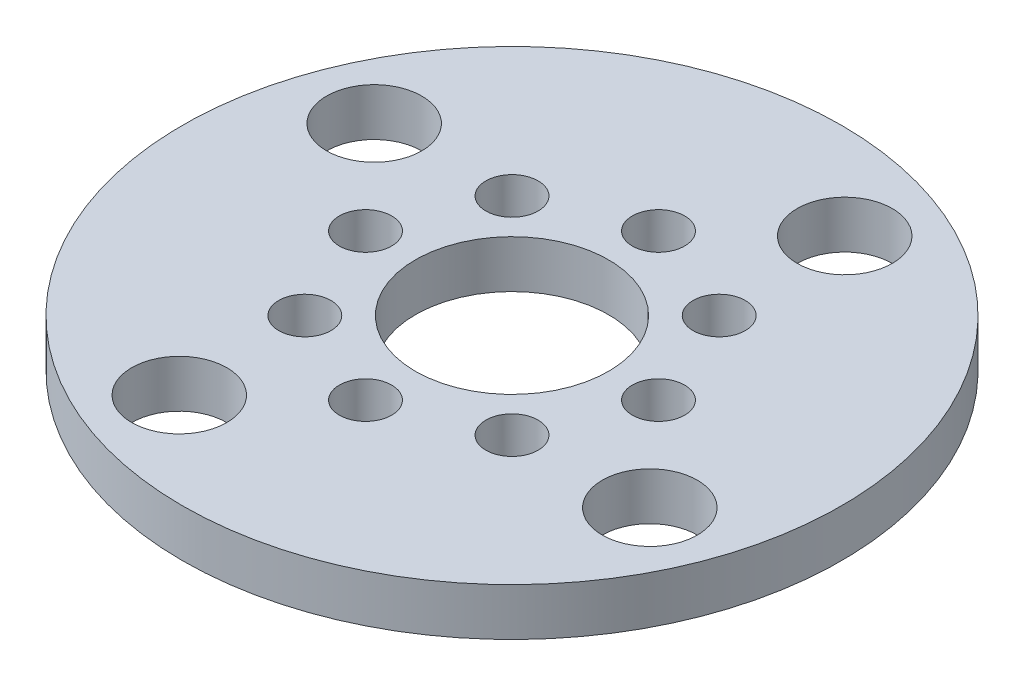
SolidWorks part; units mm, degrees
ref_plane "Front Plane" through (0, 0, 0) normal (0, 0, 1) x (1, 0, 0)
ref_plane "Top Plane" through (0, 0, 0) normal (0, 1, 0) x (1, 0, 0)
ref_plane "Right Plane" through (0, 0, 0) normal (1, 0, 0) x (0, 0, -1)
sketch "Sketch1" plane through (0, 0, 0) normal (0, 1, 0) x (1, 0, 0)
  circle A0 centre (0, 0) radius 22
  dimension "D1" = 44
extrude "Boss-Extrude1" add sketch "Sketch1" against normal blind 3.175
sketch "Sketch2" plane through (0, 0, 0) normal (0, 1, 0) x (1, 0, 0)
  circle A0 centre (0, 0) radius 6.45
  dimension "D1" = 12.9
sketch "Sketch4" plane through (0, 0, 0) normal (0, 1, 0) x (1, 0, 0)
  circle A0 centre (0, -9.779) radius 1.745
  dimension "D1" = 3.49
  dimension "D2" = 9.779
  dimension "D3" = 0
extrude "Cut-Extrude2" cut sketch "Sketch4" against normal through all both and the other way through all
extrude "Cut-Extrude4" cut sketch "Sketch2" against normal through all
pattern_circular "CirPattern1" count 8 every 45 about axis through (0, 0, 0) along (0, 1, 0) of "Cut-Extrude2"
sketch "Sketch5" plane through (0, 0, 0) normal (0, 1, 0) x (1, 0, 0)
  line L0 (0, 0) -> (17, 0) construction
  line L1 (0, 0) -> (6.5056, 15.706) construction
  circle A0 centre (0, 0) radius 17 construction
  circle A1 centre (6.5056, 15.706) radius 3.175
  dimension "D1" = 34
  dimension "D2" = 6.35
  dimension "D3" = 67.5
extrude "Cut-Extrude5" cut sketch "Sketch5" against normal through all
pattern_circular "CirPattern2" count 4 over 360 about axis through (0, 0, 0) along (0, 1, 0) of "Cut-Extrude5"
